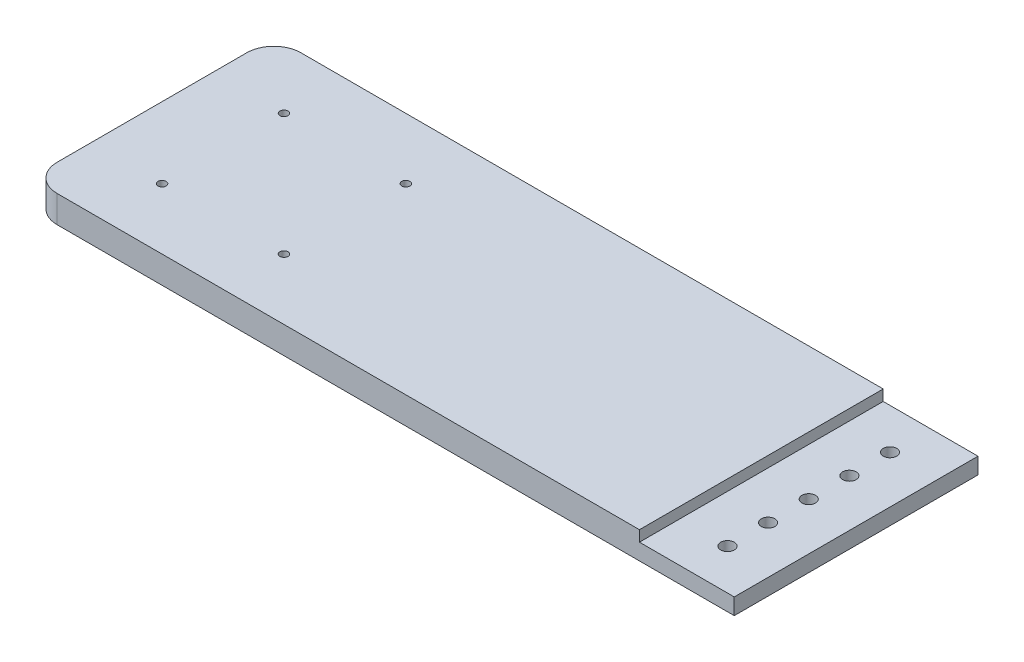
SolidWorks part; units mm, degrees
ref_plane "前视基准面" through (0, 0, 0) normal (0, 0, 1) x (1, 0, 0)
ref_plane "上视基准面" through (0, 0, 0) normal (0, 1, 0) x (1, 0, 0)
ref_plane "右视基准面" through (0, 0, 0) normal (1, 0, 0) x (0, 0, -1)
other "Configuration Table"
sketch "草图1" plane through (0, 0, 0) normal (0, 1, 0) x (1, 0, 0)
  line L1 (0, 0) -> (260, 0)
  line L2 (0, 0) -> (0, -90)
  line L3 (0, -90) -> (260, -90)
  line L4 (260, 0) -> (260, -90)
  dimension "D1" = 260
  dimension "D2" = 90
extrude "凸台-拉伸1" add sketch "草图1" along normal blind 10
sketch "草图2" plane through (0, 10, 0) normal (0, 1, 0) x (1, 0, 0)
  line L0 (0, -90) -> (260, -90) construction
  line L1 (260, 0) -> (225, 0)
  line L2 (260, 0) -> (260, -90)
  line L3 (260, -90) -> (225, -90)
  line L4 (225, 0) -> (225, -90)
  dimension "D1" = 35
extrude "切除-拉伸1" cut sketch "草图2" against normal blind 4
sketch "草图3" plane through (0, 10, 0) normal (0, 1, 0) x (1, 0, 0)
  line L0 (0, -45) -> (122.0657, -45) construction
  line L1 (26.2395, -22.5) -> (71.2395, -22.5) construction
  line L2 (26.2395, -22.5) -> (26.2395, -67.5) construction
  line L3 (26.2395, -67.5) -> (71.2395, -67.5) construction
  line L4 (71.2395, -22.5) -> (71.2395, -67.5) construction
  line L5 (0, 0) -> (0, -90) construction
  circle A0 centre (26.2395, -22.5) radius 1.5
  circle A1 centre (26.2395, -67.5) radius 1.5
  circle A2 centre (71.2395, -67.5) radius 1.5
  circle A3 centre (71.2395, -22.5) radius 1.5
  point P8 (26.2395, -45)
  dimension "D3" = 3
  dimension "D4" = 3
  dimension "D5" = 3
  dimension "D6" = 3
  dimension "D1" = 45
  dimension "D2" = 45
extrude "切除-拉伸2" cut sketch "草图3" against normal blind 10
sketch "草图4" plane through (0, 0, 0) normal (0, -1, 0) x (1, 0, 0)
  circle A0 centre (26.2395, 67.5) radius 3.5
  circle A1 centre (71.2395, 22.5) radius 1.5
  circle A2 centre (71.2395, 22.5) radius 1.5
  circle A3 centre (71.2395, 67.5) radius 1.5
  circle A4 centre (71.2395, 67.5) radius 1.5
  circle A5 centre (26.2395, 67.5) radius 1.5
  circle A6 centre (26.2395, 67.5) radius 1.5
  circle A7 centre (26.2395, 22.5) radius 1.5
  circle A8 centre (26.2395, 22.5) radius 1.5
  circle A9 centre (26.2395, 22.5) radius 3.5
  circle A10 centre (71.2395, 22.5) radius 3.5
  circle A11 centre (71.2395, 67.5) radius 3.5
  dimension "D5" = 7
  dimension "D6" = 7
  dimension "D7" = 7
  dimension "D8" = 7
  dimension "D1" = 0
  dimension "D2" = 0
  dimension "D3" = 0
  dimension "D4" = 0
extrude "切除-拉伸3" cut sketch "草图4" against normal blind 5
sketch "草图5" plane through (0, 6, 0) normal (0, 1, 0) x (1, 0, 0)
  line L0 (260, -45) -> (225, -45) construction
  line L1 (260, -90) -> (260, 0) construction
  line L2 (225, 0) -> (225, -90) construction
  line L3 (242.5, -90) -> (242.5, 0) construction
  line L4 (225, -90) -> (260, -90) construction
  line L5 (260, 0) -> (225, 0) construction
  circle A0 centre (242.5, -45) radius 2.5
  circle A1 centre (242.5, -15) radius 2.5
  circle A2 centre (242.5, -75) radius 2.5
  circle A3 centre (242.5, -30) radius 2.5
  circle A4 centre (242.5, -60) radius 2.5
  dimension "D1" = 5
  dimension "D2" = 5
  dimension "D3" = 5
  dimension "D4" = 5
  dimension "D5" = 5
  dimension "D6" = 15
  dimension "D7" = 15
  dimension "D8" = 15
  dimension "D9" = 15
  dimension "D10" = 15
extrude "切除-拉伸4" cut sketch "草图5" against normal blind 25
fillet "圆角1" radius 10 2 edges at (0, 5, 0) (0, 5, 90)
